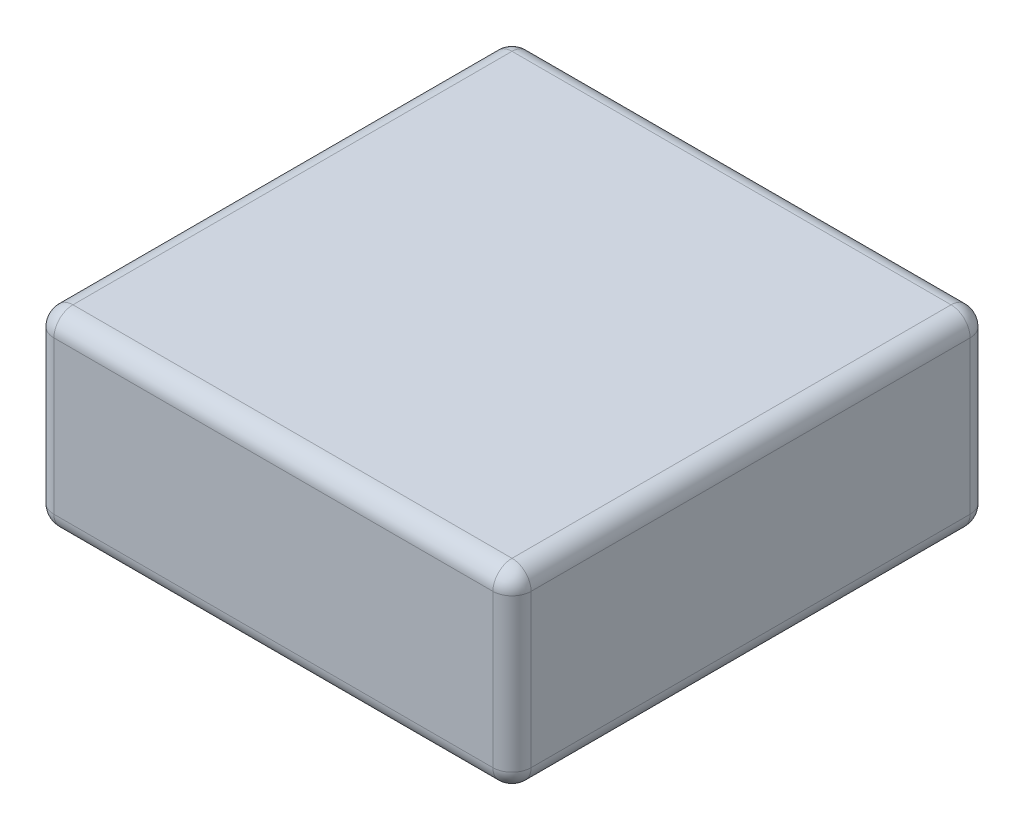
SolidWorks part; units mm, degrees
material "水"
ref_plane "前视基准面" through (0, 0, 0) normal (0, 0, 1) x (1, 0, 0)
ref_plane "上视基准面" through (0, 0, 0) normal (0, 1, 0) x (1, 0, 0)
ref_plane "右视基准面" through (0, 0, 0) normal (1, 0, 0) x (0, 0, -1)
sketch "草图1" plane through (0, 0, 0) normal (0, 1, 0) x (1, 0, 0)
  line L1 (-25, -25) -> (25, -25)
  line L2 (-25, -25) -> (-25, 25)
  line L3 (-25, 25) -> (25, 25)
  line L4 (25, -25) -> (25, 25)
  line L5 (-25, -25) -> (25, 25) construction
  line L6 (-25, 25) -> (25, -25) construction
  point P0 (0, 0)
  dimension "D1" = 50
extrude "凸台-拉伸1" add sketch "草图1" along normal mid plane 20
fillet "圆角1" radius 2 12 edges at (25, -10, 0) (0, -10, -25) (-25, -10, 0) (0, -10, 25) (25, 10, 0) (0, 10, -25) (-25, 10, 0) (0, 10, 25) (25, 0, 25) (-25, 0, -25) (25, 0, -25) (-25, 0, 25)
